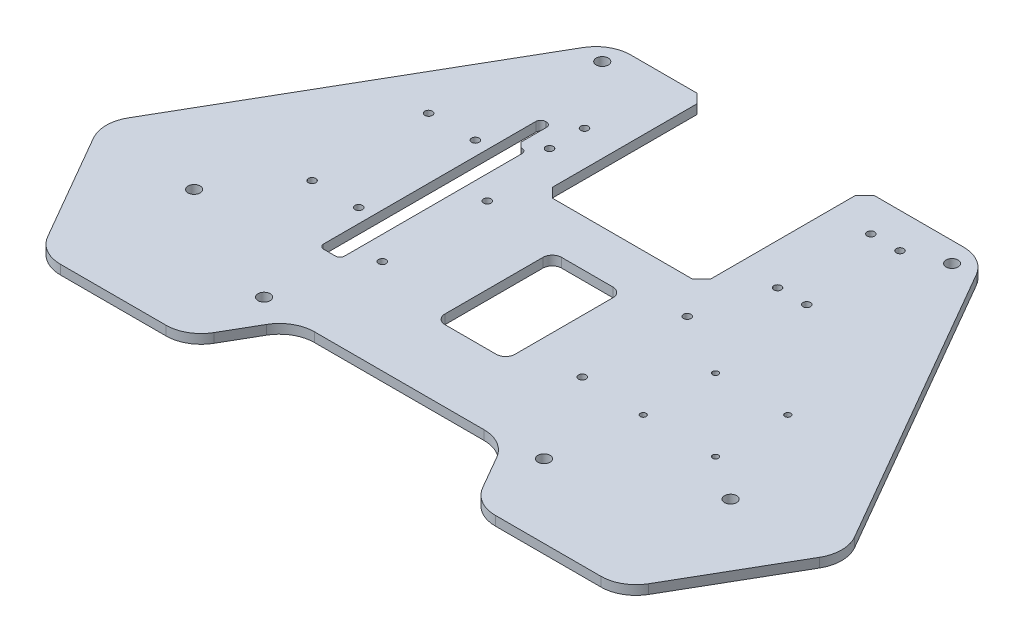
SolidWorks part; units mm, degrees
material "5052-O"
ref_plane "前基準面" through (0, 0, 0) normal (0, 0, 1) x (1, 0, 0)
ref_plane "上基準面" through (0, 0, 0) normal (0, 1, 0) x (1, 0, 0)
ref_plane "右基準面" through (0, 0, 0) normal (1, 0, 0) x (0, 0, -1)
sketch "草圖1" plane through (0, 0, 0) normal (0, 1, 0) x (1, 0, 0)
  line L0 (124.5299, -61.4359) -> (-124.5299, -61.4359)
  line L1 (80, 138.5641) -> (-80, 138.5641)
  line L2 (-80, 138.5641) -> (-160, 0)
  line L3 (-160, 0) -> (-124.5299, -61.4359)
  line L5 (124.5299, -61.4359) -> (160, 0)
  line L6 (160, 0) -> (80, 138.5641)
  line L7 (-57.4456, -138.5641) -> (92.5544, -138.5641) [skipped]
  circle A0 centre (0, 0) radius 138.5641 construction
  dimension "D1" = 160
  dimension "D2" = 200
extrude "填料-伸長1" add sketch "草圖1" along normal blind 4
sketch "草圖34" plane through (0, 4, -5) normal (0, -1, 0) x (1, 0, 0)
  circle A0 centre (-60, 35) radius 2.6
  circle A1 centre (-115, 10) radius 2.6
  circle A3 centre (-75, -125) radius 2.6
  point P0 (-75, -125)
  point P2 (-115, 10)
  point P4 (-60, 35)
  dimension "D9" = 5.2
  dimension "D10" = 5.2
  dimension "D12" = 5.2
  dimension "D2" = 75
  dimension "D3" = 130
  dimension "D6" = 60
  dimension "D7" = 30
  dimension "D8" = 115
  dimension "D13" = 5
extrude "除料-伸長2" cut sketch "草圖34" along normal through all
mirror "鏡射1" about plane through (0, 0, 0) normal (1, 0, 0) of "除料-伸長2"
sketch "草圖35" plane through (0, 4, 0) normal (0, 1, 0) x (1, 0, 0)
  line L0 (-124.5299, -61.4359) -> (124.5299, -61.4359) construction
  line L1 (45, -32.0577) -> (-45, -32.0577)
  line L2 (-45, -32.0577) -> (-90, -110)
  line L3 (-90, -110) -> (-45, -187.9423)
  line L4 (-45, -187.9423) -> (45, -187.9423)
  line L5 (45, -187.9423) -> (90, -110)
  line L6 (90, -110) -> (45, -32.0577)
  line L7 (0, 0) -> (0, -110) construction
  circle A0 centre (0, -110) radius 77.9423 construction
  dimension "D1" = 110
  dimension "D2" = 90
extrude "除料-伸長3" cut sketch "草圖35" against normal through all
fillet "圓角2" radius 15 10 edges at (80, 2, -138.5641) (160, 2, 0) (124.5299, 2, 61.4359) (61.9615, 2, 61.4359) (45, 2, 32.0577) (-61.9615, 2, 61.4359) (-124.5299, 2, 61.4359) (-160, 2, 0) (-80, 2, -138.5641) (-45, 2, 32.0577)
sketch "草圖37" plane through (0, 4, 0) normal (0, 1, 0) x (1, 0, 0)
  line L0 (71.3397, 138.5641) -> (-71.3397, 138.5641) construction
  circle A0 centre (37.87, 8.5641) radius 1.6
  point P4 (0, 138.5641)
  dimension "D1" = 37.87
  dimension "D2" = 3.2
  dimension "D3" = 130
extrude "除料-伸長5" cut sketch "草圖37" against normal through all
pattern_linear "直線複製排列1" count 2 spacing 85.74 along (-1, 0, 0) count 2 spacing 45 along (0, 0, -1) of "除料-伸長5"
sketch "草圖38" plane through (0, 4, 0) normal (0, 1, 0) x (1, 0, 0)
  line L0 (71.3397, 138.5641) -> (-71.3397, 138.5641) construction
  circle A0 centre (-73, 73.5641) radius 1.6
  point P4 (0, 138.5641)
  dimension "D1" = 65
  dimension "D3" = 3.2
  dimension "D2" = 73
extrude "除料-伸長6" cut sketch "草圖38" against normal through all
pattern_linear "直線複製排列2" count 2 spacing 20 along (-1, 0, 0) count 2 spacing 50 along (0, 0, 1) of "除料-伸長6"
sketch "草圖39" plane through (0, 4, 0) normal (0, 1, 0) x (1, 0, 0)
  line L1 (29, 138.5641) -> (-39, 138.5641)
  line L2 (29, 138.5641) -> (29, 68.5641)
  line L3 (29, 68.5641) -> (-39, 68.5641)
  line L4 (-39, 138.5641) -> (-39, 68.5641)
  line L5 (71.3397, 138.5641) -> (-71.3397, 138.5641) construction
  point P6 (0, 138.5641)
  point P7 (-5, 138.5641)
  dimension "D1" = 5
  dimension "D2" = 68
  dimension "D3" = 70
extrude "除料-伸長7" cut sketch "草圖39" against normal through all
chamfer "導角1" distance 4 angle 45 4 edges at (-39, 2, -138.5641) (-39, 2, -68.5641) (29, 2, -68.5641) (29, 2, -138.5641)
sketch "草圖41" plane through (0, 4, 0) normal (0, 1, 0) x (1, 0, 0)
  line L0 (71.3397, 138.5641) -> (33, 138.5641) construction
  line L1 (59.1, 83.5641) -> (46.6, 83.5641) construction
  line L2 (59.1, 83.5641) -> (59.1, 123.5641) construction
  line L3 (59.1, 123.5641) -> (46.6, 123.5641) construction
  line L4 (46.6, 83.5641) -> (46.6, 123.5641) construction
  line L5 (59.1, 83.5641) -> (46.6, 123.5641) construction
  line L6 (59.1, 123.5641) -> (46.6, 83.5641) construction
  circle A0 centre (59.1, 123.5641) radius 1.6
  circle A1 centre (46.6, 123.5641) radius 1.6
  circle A2 centre (46.6, 83.5641) radius 1.6
  circle A3 centre (59.1, 83.5641) radius 1.6
  point P0 (52.85, 103.5641)
  dimension "D3" = 3.2
  dimension "D4" = 35
  dimension "D5" = 52.85
  dimension "D1" = 40
  dimension "D2" = 12.5
extrude "除料-伸長9" cut sketch "草圖41" against normal up to next
sketch "草圖42" plane through (0, 4, 0) normal (0, 1, 0) x (1, 0, 0)
  line L0 (-43, 138.5641) -> (-71.3397, 138.5641) construction
  line L1 (-39, 134.5641) -> (-39, 72.5641) construction
  circle A0 centre (-54, 101.3841) radius 1.6
  circle A1 centre (-54, 86.3841) radius 1.6
  dimension "D1" = 37.18
  dimension "D4" = 3.2
  dimension "D2" = 15
  dimension "D3" = 15
extrude "除料-伸長10" cut sketch "草圖42" against normal through all
sketch "草圖43" plane through (0, 4, 0) normal (0, 1, 0) x (1, 0, 0)
  line L0 (-35, 68.5641) -> (25, 68.5641) construction
  line L1 (-15, 48.5641) -> (15, 48.5641)
  line L2 (-15, 48.5641) -> (-15, -1.4359)
  line L3 (-15, -1.4359) -> (15, -1.4359)
  line L4 (15, 48.5641) -> (15, -1.4359)
  line L5 (-15, 48.5641) -> (15, -1.4359) construction
  line L6 (-15, -1.4359) -> (15, 48.5641) construction
  point P0 (0, 23.5641)
  dimension "D1" = 30
  dimension "D2" = 50
  dimension "D3" = 45
extrude "除料-伸長11" cut sketch "草圖43" against normal up to next
fillet "圓角3" radius 4 4 edges at (-15, 2, -48.5641) (15, 2, -48.5641) (15, 2, 1.4359) (-15, 2, 1.4359)
sketch "草圖44" plane through (0, 4, 0) normal (0, 1, 0) x (1, 0, 0)
  line L1 (-58, 80.5641) -> (-67, 80.5641)
  line L2 (-58, 80.5641) -> (-58, 0.5641)
  line L3 (-58, 0.5641) -> (-67, 0.5641)
  line L4 (-67, 80.5641) -> (-67, 0.5641)
  line L6 (-39, 134.5641) -> (-39, 72.5641) construction
  line L9 (-35, 68.5641) -> (25, 68.5641) construction
  dimension "D1" = 9
  dimension "D2" = 80
  dimension "D3" = 19
  dimension "D4" = 12
extrude "除料-伸長12" cut sketch "草圖44" against normal up to next
hole_wizard "M3x0.5 螺紋孔1" positions "草圖46" profile "草圖47" tap size "M3x0.5" standard "Ansi Metric" end condition through all
sketch "草圖46" plane through (0, 4, 0) normal (0, 1, 0) x (1, 0, 0)
  line L1 (96, 7.5641) -> (65, 7.5641) construction
  line L2 (96, 7.5641) -> (96, 38.5641) construction
  line L3 (96, 38.5641) -> (65, 38.5641) construction
  line L4 (65, 7.5641) -> (65, 38.5641) construction
  line L6 (15, 2.5641) -> (15, 44.5641) construction
  line L8 (11, 48.5641) -> (-11, 48.5641) construction
  point P0 (96, 7.5641)
  point P2 (65, 7.5641)
  point P4 (65, 38.5641)
  point P6 (96, 38.5641)
  dimension "D1" = 31
  dimension "D2" = 31
  dimension "D3" = 10
  dimension "D4" = 50
sketch "草圖47" plane through (96, 4, -7.5641) normal (1, 0, 0) x (0, 0, 1)
  line L0 (0, 0) -> (0, 4)
  line L1 (0, 4) -> (1.25, 4)
  line L2 (1.25, 4) -> (1.25, 0)
  line L5 (1.25, 0) -> (0, 0)
  line L11 (0, -6.35) -> (0, 107.95) construction
  dimension "貫穿螺孔鑽直徑" = 2.5
  dimension "貫穿螺孔鑽深度" = 4
cosmetic thread "鑽孔螺紋1" parameters "D2"=3
cosmetic thread "鑽孔螺紋2" parameters "D2"=3
cosmetic thread "鑽孔螺紋3" parameters "D2"=3
cosmetic thread "鑽孔螺紋4" parameters "D2"=3
sketch "草圖48" plane through (0, 4, 0) normal (0, 1, 0) x (1, 0, 0)
  line L0 (-58, 80.5641) -> (-67, 80.5641) construction
  line L1 (-62.5, 80.5641) -> (-67, 80.5641)
  line L2 (-62.5, 80.5641) -> (-62.5, 95.5641)
  line L3 (-62.5, 95.5641) -> (-67, 95.5641)
  line L4 (-67, 80.5641) -> (-67, 95.5641)
  dimension "D1" = 4.5
  dimension "D2" = 15
extrude "除料-伸長13" cut sketch "草圖48" against normal up to next
chamfer "導角2" distance 2 angle 45 1 edges at (-62.5, 2, -80.5641)
fillet "圓角8" radius 2 5 edges at (-67, 2, -95.5641) (-62.5, 2, -95.5641) (-58, 2, -80.5641) (-67, 2, -0.5641) (-58, 2, -0.5641)
